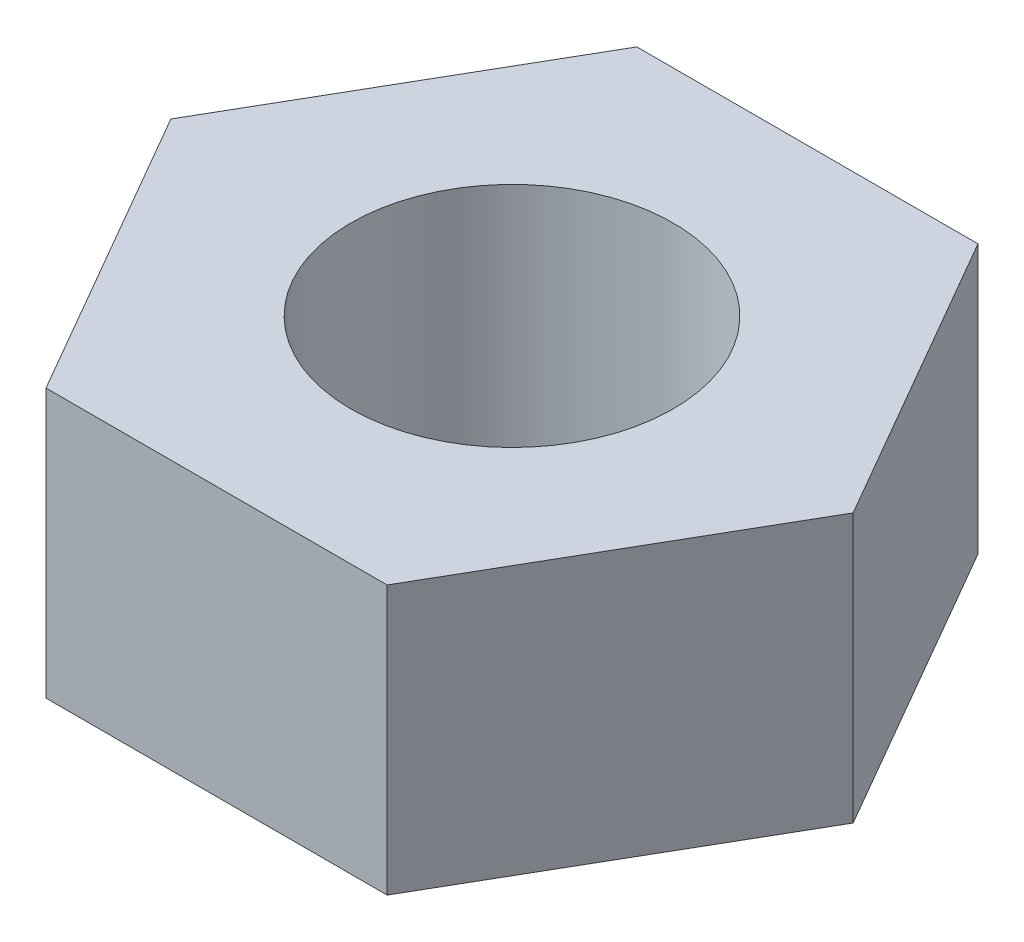
SolidWorks part; units mm, degrees
ref_plane "Front Plane" through (0, 0, 0) normal (0, 0, 1) x (1, 0, 0)
ref_plane "Top Plane" through (0, 0, 0) normal (0, 1, 0) x (1, 0, 0)
ref_plane "Right Plane" through (0, 0, 0) normal (1, 0, 0) x (0, 0, -1)
sketch "Sketch1" plane through (0, 0, 0) normal (0, 1, 0) x (1, 0, 0)
  line L1 (1.5877, 2.75) -> (-1.5877, 2.75)
  line L2 (-1.5877, 2.75) -> (-3.1754, 0)
  line L3 (-3.1754, 0) -> (-1.5877, -2.75)
  line L4 (-1.5877, -2.75) -> (1.5877, -2.75)
  line L5 (1.5877, -2.75) -> (3.1754, 0)
  line L6 (3.1754, 0) -> (1.5877, 2.75)
  circle A0 centre (0, 0) radius 2.75 construction
  circle A1 centre (0, 0) radius 1.5
  point P11 (-0.0679, 0)
  dimension "D1" = 5.5
  dimension "D2" = 3
extrude "Boss-Extrude1" add sketch "Sketch1" along normal mid plane 2.5
